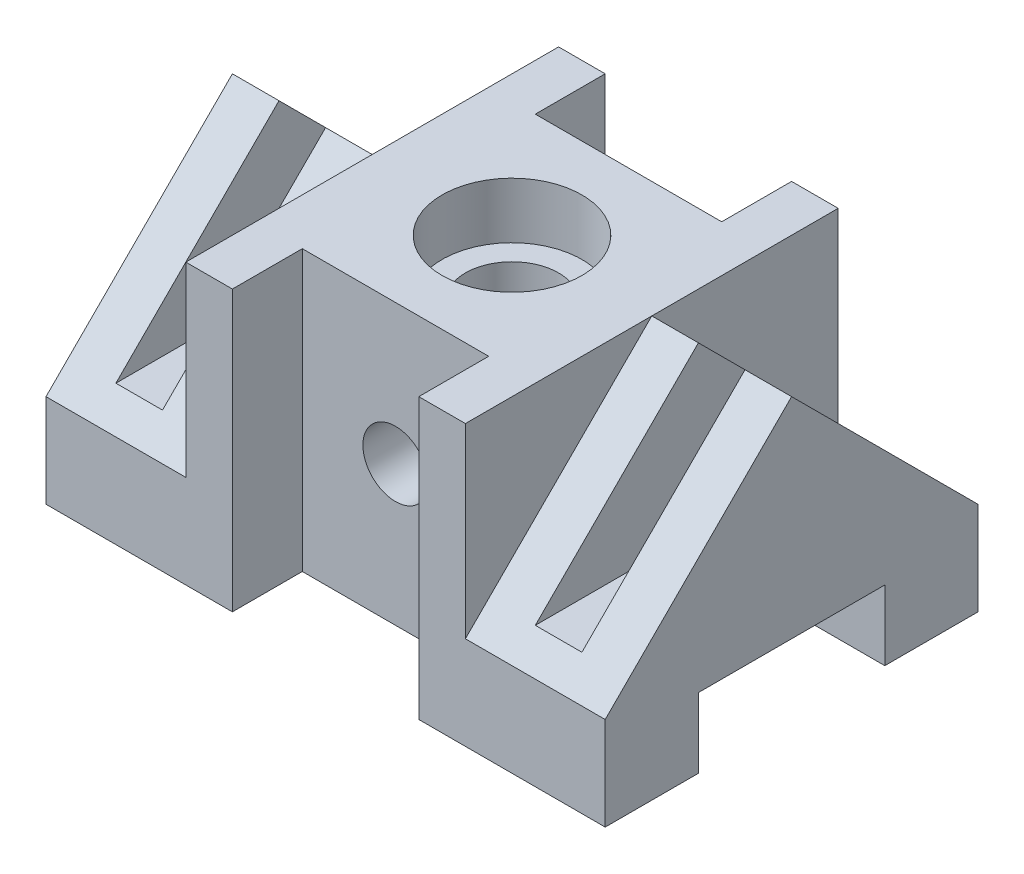
SolidWorks part; units mm, degrees
ref_plane "Front Plane" through (0, 0, 0) normal (0, 0, 1) x (1, 0, 0)
ref_plane "Top Plane" through (0, 0, 0) normal (0, 1, 0) x (1, 0, 0)
ref_plane "Right Plane" through (0, 0, 0) normal (1, 0, 0) x (0, 0, -1)
sketch "Sketch1" plane through (0, 0, 0) normal (0, 1, 0) x (1, 0, 0)
  line L0 (-7.9061, 42.3131) -> (-17.9061, 42.3131)
  line L1 (-17.9061, 42.3131) -> (-17.9061, -37.6869)
  line L2 (-17.9061, -37.6869) -> (-7.9061, -37.6869)
  line L3 (-7.9061, -37.6869) -> (-7.9061, -22.6869)
  line L4 (-7.9061, -22.6869) -> (32.0939, -22.6869)
  line L5 (32.0939, -22.6869) -> (32.0939, -37.6869)
  line L6 (32.0939, -37.6869) -> (42.0939, -37.6869)
  line L7 (42.0939, -37.6869) -> (42.0939, 42.3131)
  line L8 (42.0939, 42.3131) -> (32.0939, 42.3131)
  line L9 (32.0939, 42.3131) -> (32.0939, 27.3131)
  line L10 (32.0939, 27.3131) -> (-7.9061, 27.3131)
  line L11 (-7.9061, 27.3131) -> (-7.9061, 42.3131)
  dimension "D1" = 40
  dimension "D2" = 80
  dimension "D3" = 10
  dimension "D4" = 10
  dimension "D5" = 15
extrude "Boss-Extrude1" add sketch "Sketch1" against normal blind 60
sketch "Sketch3" plane through (0, 0, 37.6869) normal (0, 0, 1) x (1, 0, 0)
  line L0 (-17.9061, -40) -> (-47.9061, -40)
  line L1 (-17.9061, -60) -> (-17.9061, 0) construction
  line L2 (-47.9061, -40) -> (-47.9061, -60)
  line L3 (-47.9061, -60) -> (-17.9061, -60)
  line L4 (-17.9061, -60) -> (-17.9061, -40)
  line L5 (42.0939, -40) -> (72.0939, -40)
  line L6 (42.0939, -60) -> (42.0939, 0) construction
  line L7 (72.0939, -40) -> (72.0939, -60)
  line L8 (72.0939, -60) -> (42.0939, -60)
  line L9 (42.0939, -60) -> (42.0939, -40)
  dimension "D1" = 30
  dimension "D2" = 20
  dimension "D3" = 30
extrude "Boss-Extrude2" add sketch "Sketch3" against normal blind 80
sketch "Sketch4" plane through (-47.9061, 0, 0) normal (-1, 0, 0) x (0, 0, 1)
  line L0 (-22.3131, -60) -> (-22.3131, -45)
  line L1 (-42.3131, -60) -> (37.6869, -60) construction
  line L2 (-22.3131, -45) -> (17.6869, -45)
  line L3 (17.6869, -45) -> (17.6869, -60)
  line L4 (17.6869, -60) -> (-22.3131, -60)
  line L5 (-42.3131, -40) -> (37.6869, -40) construction
  point P8 (-2.3131, -40)
  point P9 (-2.3131, -60)
  dimension "D1" = 15
  dimension "D2" = 40
extrude "Cut-Extrude1" cut sketch "Sketch4" against normal through all
sketch "Sketch5" plane through (-47.9061, 0, 0) normal (-1, 0, 0) x (0, 0, 1)
  line L0 (-42.3131, -40) -> (-2.3131, 0)
  line L1 (-2.3131, 0) -> (37.6869, -40)
  line L2 (37.6869, -40) -> (-42.3131, -40)
extrude "Boss-Extrude3" add sketch "Sketch5" against normal blind 30
sketch "Sketch6" plane through (72.0939, 0, 0) normal (1, 0, 0) x (0, 0, -1)
  line L0 (-37.6869, -40) -> (2.3131, 0)
  line L1 (2.3131, 0) -> (42.3131, -40)
  line L2 (42.3131, -40) -> (-37.6869, -40)
extrude "Boss-Extrude4" add sketch "Sketch6" against normal blind 30
ref_plane "Plane1" through (0, 0, -2.3131) normal (0, 0, 1) x (1, 0, 0)
sketch "Sketch8" plane through (0, 0, -2.3131) normal (0, 0, 1) x (1, 0, 0)
  line L0 (-37.9061, 0) -> (-37.9061, -35)
  line L1 (-17.9061, 0) -> (-47.9061, 0) construction
  line L2 (-37.9061, -35) -> (-27.9061, -35)
  line L3 (-27.9061, -35) -> (-27.9061, 0)
  line L4 (-27.9061, 0) -> (-37.9061, 0)
  line L5 (-47.9061, -40) -> (-47.9061, 0) construction
  line L6 (-17.9061, -40) -> (-17.9061, 0) construction
  dimension "D1" = 10
  dimension "D2" = 10
  dimension "D3" = 35
extrude "Cut-Extrude2" cut sketch "Sketch8" against normal mid plane 122
sketch "Sketch9" plane through (0, 0, -2.3131) normal (0, 0, 1) x (1, 0, 0)
  line L0 (52.0939, 0) -> (52.0939, -35)
  line L1 (42.0939, 0) -> (72.0939, 0) construction
  line L2 (52.0939, -35) -> (62.0939, -35)
  line L3 (62.0939, -35) -> (62.0939, 0)
  line L4 (62.0939, 0) -> (52.0939, 0)
  line L5 (42.0939, -40) -> (42.0939, 0) construction
  line L6 (72.0939, 0) -> (72.0939, -40) construction
  dimension "D1" = 10
  dimension "D2" = 10
  dimension "D3" = 35
extrude "Cut-Extrude3" cut sketch "Sketch9" against normal mid plane 122
sketch "Sketch10" plane through (0, 0, 22.6869) normal (0, 0, 1) x (1, 0, 0)
  line L0 (-7.9061, -60) -> (-7.9061, 0) construction
  line L1 (-7.9061, -60) -> (32.0939, -60) construction
  circle A0 centre (12.0939, -30) radius 7
  dimension "D1" = 20
  dimension "D2" = 30
extrude "Cut-Extrude4" cut sketch "Sketch10" against normal mid plane 122
ref_plane "Plane2" through (0, -10, 0) normal (0, 1, 0) x (1, 0, 0)
sketch "Sketch12" plane through (0, -10, 0) normal (0, 1, 0) x (1, 0, 0)
  line L0 (-22, 2.3131) -> (22, 2.3131) construction
  circle A0 centre (12.0939, 2.3131) radius 10
extrude "Cut-Extrude5" cut sketch "Sketch12" against normal blind 12
sketch "Sketch13" plane through (0, 0, 0) normal (0, 1, 0) x (1, 0, 0)
  line L0 (-22, 2.3131) -> (22, 2.3131) construction
  circle A0 centre (12.0939, 2.3131) radius 15
extrude "Cut-Extrude6" cut sketch "Sketch13" against normal blind 12
